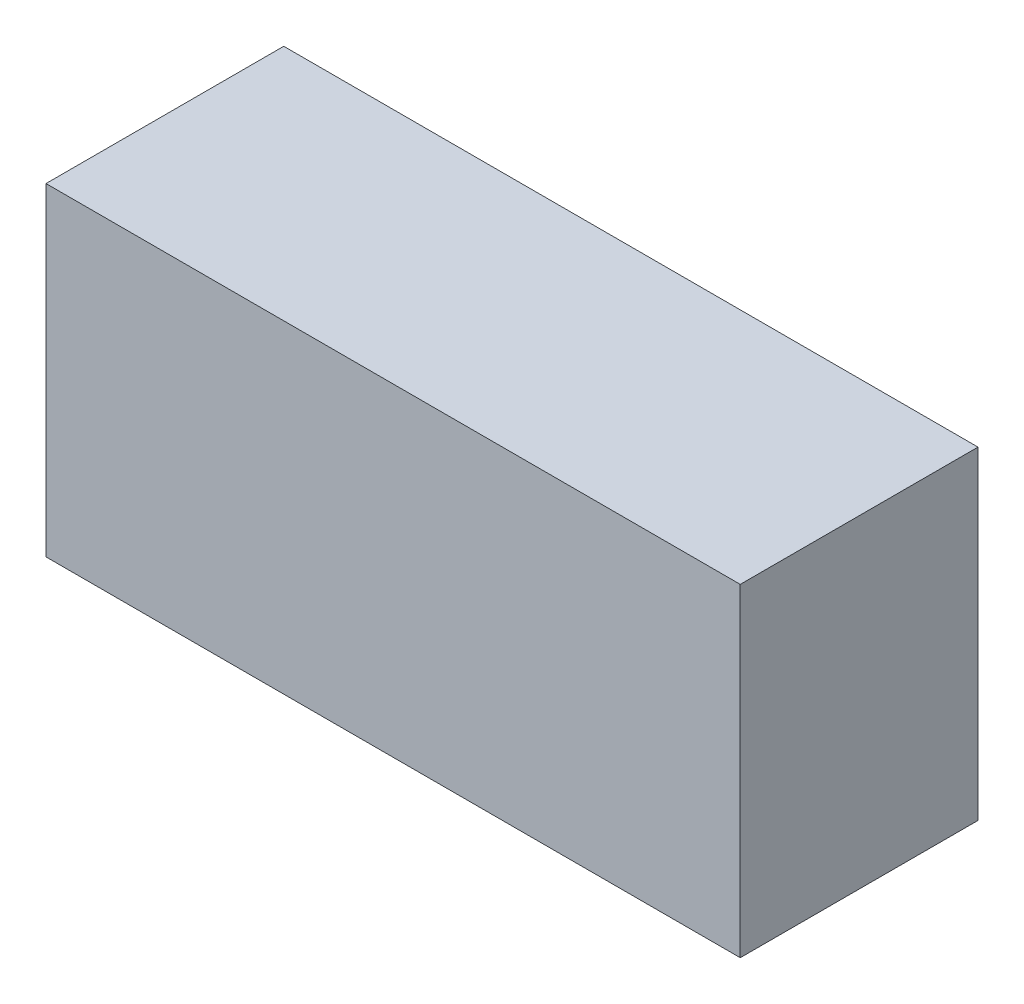
SolidWorks part; units mm, degrees
ref_plane "Front Plane" through (0, 0, 0) normal (0, 0, 1) x (1, 0, 0)
ref_plane "Top Plane" through (0, 0, 0) normal (0, 1, 0) x (1, 0, 0)
ref_plane "Right Plane" through (0, 0, 0) normal (1, 0, 0) x (0, 0, -1)
sketch "Sketch1" plane through (0, 0, 0) normal (0, 1, 0) x (1, 0, 0)
  line L1 (-36.5, -12.5) -> (36.5, -12.5)
  line L2 (-36.5, -12.5) -> (-36.5, 12.5)
  line L3 (-36.5, 12.5) -> (36.5, 12.5)
  line L4 (36.5, -12.5) -> (36.5, 12.5)
  line L5 (-36.5, -12.5) -> (36.5, 12.5) construction
  line L6 (-36.5, 12.5) -> (36.5, -12.5) construction
  point P0 (0, 0)
  dimension "D1" = 25
  dimension "D2" = 73
extrude "Boss-Extrude1" add sketch "Sketch1" along normal blind 34
